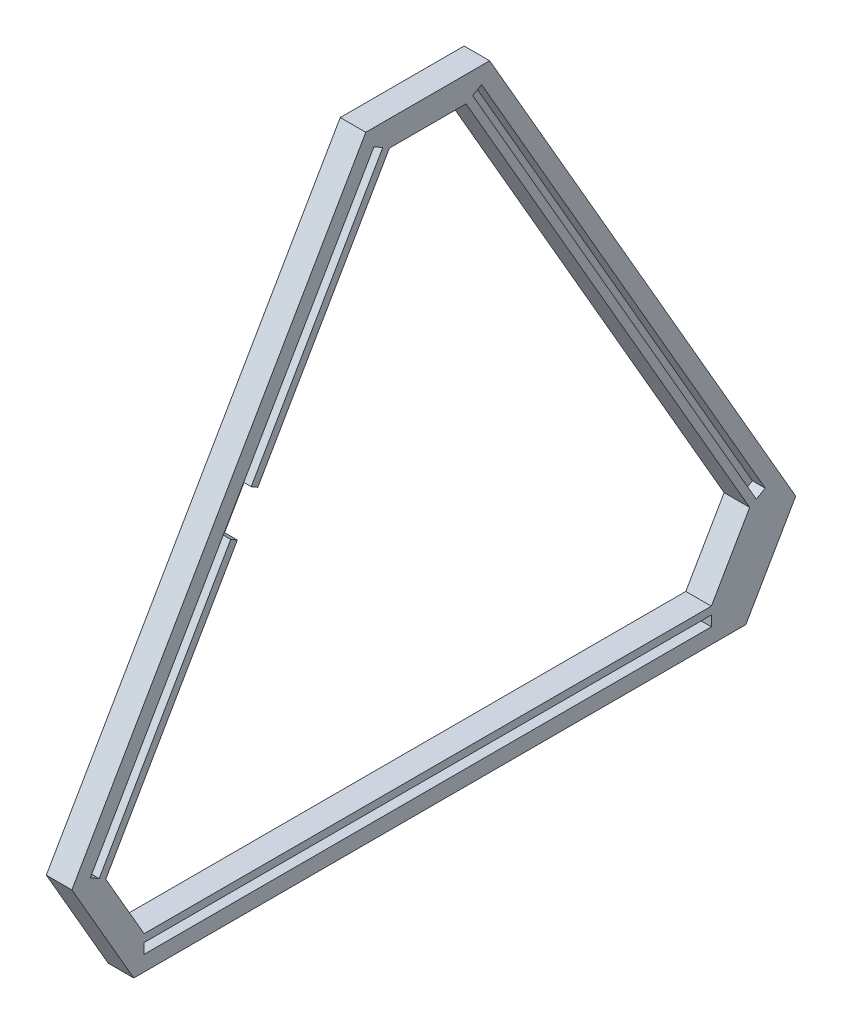
SolidWorks part; units mm, degrees
ref_plane "Front Plane" through (0, 0, 0) normal (0, 0, 1) x (1, 0, 0)
ref_plane "Top Plane" through (0, 0, 0) normal (0, 1, 0) x (1, 0, 0)
ref_plane "Right Plane" through (0, 0, 0) normal (1, 0, 0) x (0, 0, -1)
sketch "Sketch3" plane through (0, 0, 0) normal (1, 0, 0) x (0, 0, -1)
  line L0 (0, 0) -> (141, 0) construction
  line L1 (141, 0) -> (70.5, 122.1096) construction
  line L2 (70.5, 122.1096) -> (0, 0) construction
  line L3 (7.5, 12.9904) -> (15, 0)
  line L4 (7.5, 12.9904) -> (0, 0) construction
  line L5 (0, 0) -> (15, 0) construction
  line L6 (15, 0) -> (15, -1.5)
  line L7 (15, -1.5) -> (126, -1.5)
  line L8 (70.5, 122.1096) -> (70.5, 0) construction
  line L9 (133.5, 12.9904) -> (126, 0)
  line L10 (126, -1.5) -> (126, 0)
  line L11 (7.5, 12.9904) -> (6.201, 13.7404)
  line L12 (6.201, 13.7404) -> (61.701, 109.8692)
  line L13 (61.701, 109.8692) -> (63, 109.1192)
  line L14 (63, 109.1192) -> (78, 109.1192)
  line L15 (79.299, 109.8692) -> (134.799, 13.7404)
  line L16 (134.799, 13.7404) -> (133.5, 12.9904)
  line L17 (78, 109.1192) -> (79.299, 109.8692)
  line L18 (58.3812, 114.1192) -> (0.8605, 14.4904)
  line L19 (0.8605, 14.4904) -> (12.9793, -6.5)
  line L20 (12.9793, -6.5) -> (132.75, -6.5)
  line L21 (132.75, -6.5) -> (142.5042, 10.3947)
  line L22 (142.5042, 10.3947) -> (82.6188, 114.1192)
  line L23 (82.6188, 114.1192) -> (58.3812, 114.1192)
  line L24 (129.75, 6.4952) -> (137.6271, 1.9474) construction
  line L25 (70.5, -1.5) -> (70.5, -6.5) construction
  line L26 (78, 109.1192) -> (78, 114.1192) construction
  dimension "D1" = 141
  dimension "D2" = 1.5
  dimension "D3" = 111
  dimension "D4" = 15
  dimension "D5" = 5
  dimension "D6" = 5
  dimension "D7" = 5
  dimension "D8" = 5
  dimension "D9" = 5
  dimension "D10" = 9.0957
extrude "Boss-Extrude1" add sketch "Sketch3" along normal blind 155
sketch "Sketch4" plane through (0, 3.25, 5.6292) normal (0, 0.5, 0.866) x (1, 0, 0)
  line L0 (155, 126) -> (0, 126) construction
  line L1 (5.5, 126) -> (149.5, 126)
  line L2 (5.5, 126) -> (5.5, 15)
  line L3 (5.5, 15) -> (149.5, 15)
  line L4 (149.5, 126) -> (149.5, 15)
  line L5 (155, 15) -> (0, 15) construction
  line L6 (5.5, 70.5) -> (0, 70.5) construction
  line L7 (0, 128.0207) -> (0, 12.9793) construction
  line L8 (149.5, 70.5) -> (155, 70.5) construction
  line L9 (155, 128.0207) -> (155, 12.9793) construction
  dimension "D1" = 144
extrude "Cut-Extrude1" cut sketch "Sketch4" against normal up to surface (5 mm away) up to face at (77.5, 61.8048, -33.951)
sketch "Sketch5" plane through (0, 64.3048, -111.3792) normal (0, 0.5, -0.866) x (-1, 0, 0)
  line L0 (-155, -62.25) -> (-77.5, -2.3646) construction
  line L1 (-77.5, -2.3646) -> (-155, 57.5207) construction
  line L2 (0, 57.5207) -> (-77.5, -2.3646) construction
  line L3 (-77.5, -2.3646) -> (0, -62.25) construction
  circle A0 centre (-77.5, -2.3646) radius 38.5
  dimension "D1" = 77
extrude "Cut-Extrude2" cut sketch "Sketch5" against normal blind 10
sketch "Sketch6" plane through (155, 0, 0) normal (1, 0, 0) x (0, 0, -1)
  line L6 (82.6188, 114.1192) -> (58.3812, 114.1192)
  line L7 (58.3812, 114.1192) -> (0.8605, 14.4904)
  line L8 (0.8605, 14.4904) -> (12.9793, -6.5)
  line L9 (12.9793, -6.5) -> (132.75, -6.5)
  line L10 (132.75, -6.5) -> (142.5042, 10.3947)
  line L11 (142.5042, 10.3947) -> (82.6188, 114.1192)
  line L12 (82.6188, 114.1192) -> (58.3812, 114.1192)
  line L13 (58.3812, 114.1192) -> (0.8605, 14.4904)
  line L14 (0.8605, 14.4904) -> (12.9793, -6.5)
  line L15 (12.9793, -6.5) -> (132.75, -6.5)
  line L16 (132.75, -6.5) -> (142.5042, 10.3947)
  line L17 (142.5042, 10.3947) -> (82.6188, 114.1192)
  dimension "D1" = 0
extrude "Boss-Extrude2" add sketch "Sketch6" along normal blind 5 separate body
sketch "Sketch7" plane through (160, 0, 0) normal (1, 0, 0) x (0, 0, -1)
  line L2 (78, 109.1192) -> (63, 109.1192) construction
  line L4 (126, 0) -> (133.5, 12.9904) construction
  line L20 (7.5, 12.9904) -> (15, 0) construction
  line L23 (63, 109.1192) -> (7.5, 12.9904)
  line L24 (15, 0) -> (126, 0)
  line L25 (78, 109.1192) -> (63, 109.1192)
  line L26 (133.5, 12.9904) -> (78, 109.1192)
  line L27 (126, 0) -> (133.5, 12.9904)
  line L31 (7.5, 12.9904) -> (15, 0)
extrude "Cut-Extrude3" cut sketch "Sketch7" against normal blind 5
sketch "Sketch8" plane through (160, 0, 0) normal (1, 0, 0) x (0, 0, -1)
  line L0 (6.201, 13.7404) -> (61.701, 109.8692)
  line L1 (61.701, 109.8692) -> (59.9689, 110.8692)
  line L3 (59.9689, 110.8692) -> (4.4689, 14.7404)
  line L5 (4.4689, 14.7404) -> (6.201, 13.7404)
  line L6 (126, -1.5) -> (126, 0) construction
  line L7 (15, -1.5) -> (126, -1.5)
  line L8 (15, -1.5) -> (15, -3.5)
  line L9 (15, -3.5) -> (126, -3.5)
  line L10 (126, -1.5) -> (126, -3.5)
  line L11 (79.299, 109.8692) -> (134.799, 13.7404)
  line L12 (134.799, 13.7404) -> (136.5311, 14.7404)
  line L13 (136.5311, 14.7404) -> (81.0311, 110.8692)
  line L14 (81.0311, 110.8692) -> (79.299, 109.8692)
  dimension "D1" = 2
extrude "Cut-Extrude4" cut sketch "Sketch8" against normal blind 2.5
sketch "Sketch10" plane through (160, 0, 0) normal (1, 0, 0) x (0, 0, -1)
  line L0 (35.25, 61.0548) -> (29.6208, 64.3048) construction
  line L1 (63, 109.1192) -> (7.5, 12.9904) construction
  line L2 (58.3812, 114.1192) -> (0.8605, 14.4904) construction
  line L3 (37.25, 64.5189) -> (33.25, 57.5907)
  line L4 (33.25, 57.5907) -> (31.951, 58.3407)
  line L5 (6.201, 13.7404) -> (61.701, 109.8692) construction
  line L6 (31.951, 58.3407) -> (35.951, 65.2689)
  line L7 (37.25, 64.5189) -> (35.951, 65.2689)
  point P13 (33.951, 61.8048)
  dimension "D1" = 8
extrude "Cut-Extrude5" cut sketch "Sketch10" against normal blind 2.5
delete or keep bodies "Body-Delete2" type delete bodies bodies 103
